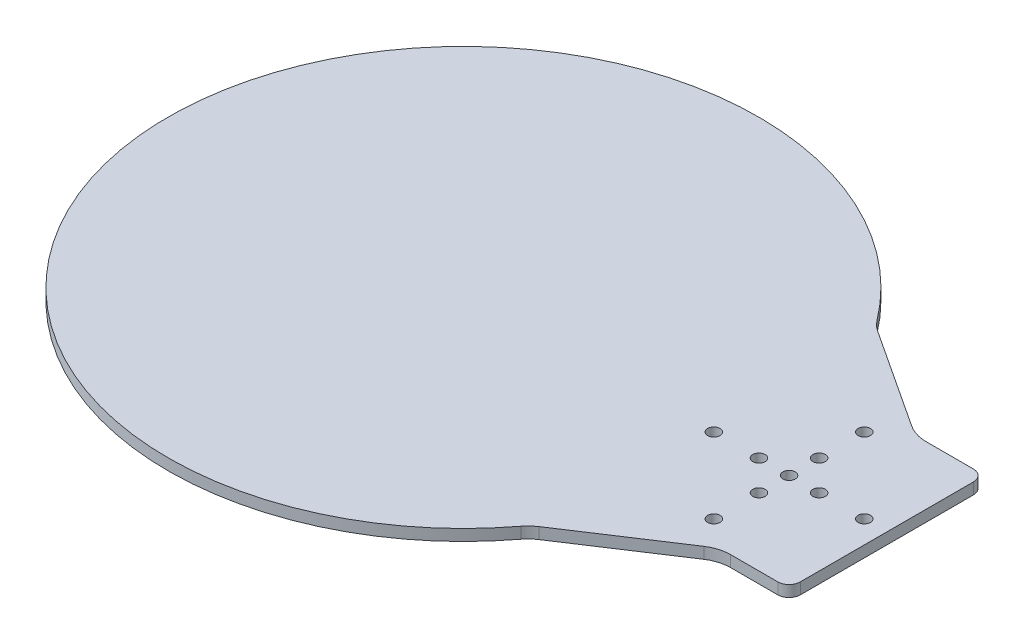
SolidWorks part; units mm, degrees
ref_plane "Front Plane" through (0, 0, 0) normal (0, 0, 1) x (1, 0, 0)
ref_plane "Top Plane" through (0, 0, 0) normal (0, 1, 0) x (1, 0, 0)
ref_plane "Right Plane" through (0, 0, 0) normal (1, 0, 0) x (0, 0, -1)
sketch "Sketch1" plane through (0, 0, 0) normal (0, 1, 0) x (1, 0, 0)
  line L0 (0, 0) -> (162.6239, 0) construction
  line L1 (74.0692, -26) -> (112.579, -26)
  line L2 (112.579, -26) -> (112.579, 26)
  line L3 (74.0692, 26) -> (112.579, 26)
  arc A0 (74.0692, 26) -> (74.0692, -26) centre (0, 0) ccw
  circle A1 centre (86.579, 0) radius 1.65
  circle A2 centre (94.579, 0) radius 1.65
  circle A3 centre (106.579, 0) radius 1.65
  circle A4 centre (86.579, -8) radius 1.65
  circle A5 centre (86.579, -20) radius 1.65
  circle A6 centre (78.579, 0) radius 1.65
  circle A7 centre (66.579, 0) radius 1.65
  circle A8 centre (86.579, 8) radius 1.65
  circle A9 centre (86.579, 20) radius 1.65
  point P24 (86.579, 0)
  point P28 (112.579, 0)
  dimension "D1" = 157
  dimension "D3" = 3.3
  dimension "D5" = 3.3
  dimension "D2" = 86.579
  dimension "D4" = 8
  dimension "D8" = 6
  dimension "D9" = 6
  dimension "D6" = 2
  dimension "D7" = 4
extrude "Boss-Extrude1" add sketch "Sketch1" along normal blind 3
sketch "Sketch2" plane through (0, 3, 0) normal (0, 1, 0) x (1, 0, 0)
  line L1 (112.579, 26) -> (74.0692, 26) construction
  line L3 (94.0692, 26) -> (74.0692, 26)
  line L4 (63.6101, 46) -> (94.0692, 26)
  line L5 (0, 0) -> (38.3553, 0) construction
  line L6 (63.6101, -46) -> (94.0692, -26)
  line L7 (94.0692, -26) -> (74.0692, -26)
  arc A0 (74.0692, 26) -> (74.0692, -26) centre (0, 0) ccw construction
  arc A1 (74.0692, 26) -> (63.6101, 46) centre (0, 0) ccw
  arc A2 (74.0692, -26) -> (63.6101, -46) centre (0, 0) cw
  arc M9 (74.0692, 26) -> (74.0692, -26) centre (0, 0) ccw
  line M10 (74.0692, -26) -> (112.579, -26)
  line M12 (112.579, 26) -> (74.0692, 26)
  dimension "D1" = 20
  dimension "D2" = 20
extrude "Boss-Extrude2" add sketch "Sketch2" against normal blind 3 contours L6 M9 M10 | L4 M9 M12
fillet "Fillet1" radius 10 4 edges at (94.0692, 1.5, 26) (63.6101, 1.5, 46) (63.6101, 1.5, -46) (94.0692, 1.5, -26)
fillet "Fillet2" radius 3 2 edges at (112.579, 1.5, -26) (112.579, 1.5, 26)
